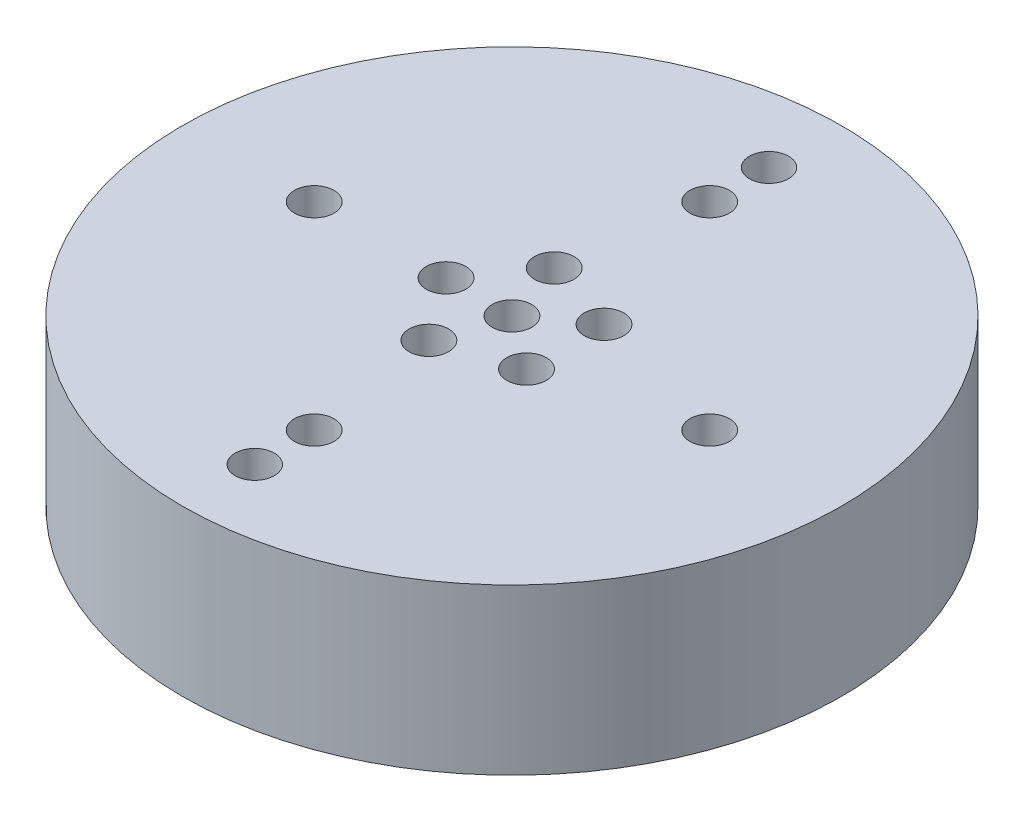
SolidWorks part; units mm, degrees
material "Perspex (TM) GS Acrylic Cast Sheet"
ref_plane "Front Plane" through (0, 0, 0) normal (0, 0, 1) x (1, 0, 0)
ref_plane "Top Plane" through (0, 0, 0) normal (0, 1, 0) x (1, 0, 0)
ref_plane "Right Plane" through (0, 0, 0) normal (1, 0, 0) x (0, 0, -1)
sketch "Sketch1" plane through (0, 0, 0) normal (0, 1, 0) x (1, 0, 0)
  circle A0 centre (0, 0) radius 12.7
  dimension "D1" = 25.4
extrude "Boss-Extrude1" add sketch "Sketch1" along normal blind 6.35
sketch "Sketch2" plane through (0, 0, 0) normal (0, -1, 0) x (1, 0, 0)
  circle A0 centre (0, 0) radius 9.271
  dimension "D1" = 18.542
extrude "Cut-Extrude1" cut sketch "Sketch2" against normal blind 3.175
hole_wizard "#1-72 Tapped Hole1" positions "3DSketch3" profile "Sketch5" tap size "#1-72" standard "ANSI Inch"
sketch3d "3DSketch3"
  point P0 (9.9542, 0, 34.1371)
  point P2 (0, 0, 9.906)
  point P4 (0, 0, -9.906)
  point P10 (0, 0, 9.906)
sketch "Sketch5" plane through (0, 0, -9.906) normal (1, 0, 0) x (0, 0, -1)
  line L0 (0, 0) -> (0, 11.63)
  line L1 (0, 11.63) -> (0.7556, 11.176)
  line L2 (0.7556, 11.176) -> (0.7556, 0)
  line L5 (0.7556, 0) -> (0, 0)
  line L10 (0, 11.63) -> (-0.7556, 11.176) construction
  line L11 (0, -6.35) -> (0, 107.95) construction
  dimension "Tap Drill Dia." = 1.5113
  dimension "Tap Drill Depth" = 11.176
  dimension "Drill Angle" = 118
cosmetic thread "Hole Thread3" parameters "D1"=7.112, "D2"=1.8542
cosmetic thread "Hole Thread4" parameters "D1"=7.112, "D2"=1.8542
cosmetic thread "Hole Thread5" parameters "D1"=7.112, "D2"=1.8542
cosmetic thread "Hole Thread6" parameters "D1"=7.112, "D2"=1.8542
pattern_circular "CirPattern1" count 2 over 360 about axis through (0, 0, 0.0022) along (0, 1, 0) of "#1-72 Tapped Hole1"
cosmetic thread "Hole Thread7" parameters "D1"=7.112, "D2"=1.8542
cosmetic thread "Hole Thread8" parameters "D1"=7.112, "D2"=1.8542
cosmetic thread "Hole Thread9" parameters "D1"=7.112, "D2"=1.8542
cosmetic thread "Hole Thread10" parameters "D1"=7.112, "D2"=1.8542
sketch "Sketch6" plane through (0, 6.35, 0) normal (0, 1, 0) x (1, 0, 0)
  line L0 (-2.54, 0) -> (0, 0) construction
  line L1 (0, 7.62) -> (0, 0) construction
  circle A0 centre (0, 0) radius 0.762
  circle A1 centre (-2.54, 0) radius 0.762
  circle A2 centre (-0.7849, 2.4157) radius 0.762
  circle A3 centre (2.0549, 1.493) radius 0.762
  circle A4 centre (2.0549, -1.493) radius 0.762
  circle A5 centre (-0.7849, -2.4157) radius 0.762
  circle A6 centre (0, 7.62) radius 0.762
  circle A7 centre (7.62, 0) radius 0.762
  circle A8 centre (0, -7.62) radius 0.762
  circle A9 centre (-7.62, 0) radius 0.762
  point P16 (0, 0)
  point P25 (0, 0)
  dimension "D1" = 1.524
  dimension "D2" = 2.54
  dimension "D4" = 7.62
  dimension "D3" = 5
  dimension "D5" = 4
extrude "Cut-Extrude2" cut sketch "Sketch6" against normal blind 3.175
